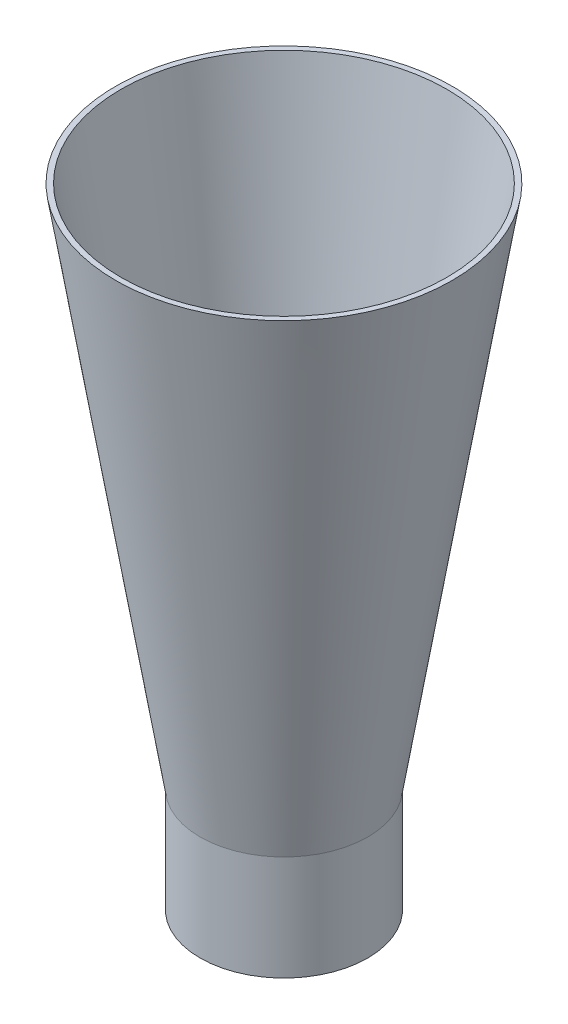
SolidWorks part; units mm, degrees
ref_plane "정면" through (0, 0, 0) normal (0, 0, 1) x (1, 0, 0)
ref_plane "윗면" through (0, 0, 0) normal (0, 1, 0) x (1, 0, 0)
ref_plane "우측면" through (0, 0, 0) normal (1, 0, 0) x (0, 0, -1)
sketch "스케치1" plane through (0, 0, 0) normal (0, 0, 1) x (1, 0, 0)
  line L0 (0, 0) -> (32.1, 0)
  line L1 (32.1, 0) -> (16, -100)
  line L2 (16, -100) -> (16, -120)
  line L3 (16, -120) -> (0, -120)
  line L4 (0, -120) -> (0, 0)
  dimension "D1" = 32.1
  dimension "D2" = 20
  dimension "D3" = 16
  dimension "D4" = 100
revolve "회전1" add sketch "스케치1" angle 360 about L4
shell "쉘1" thickness 1
